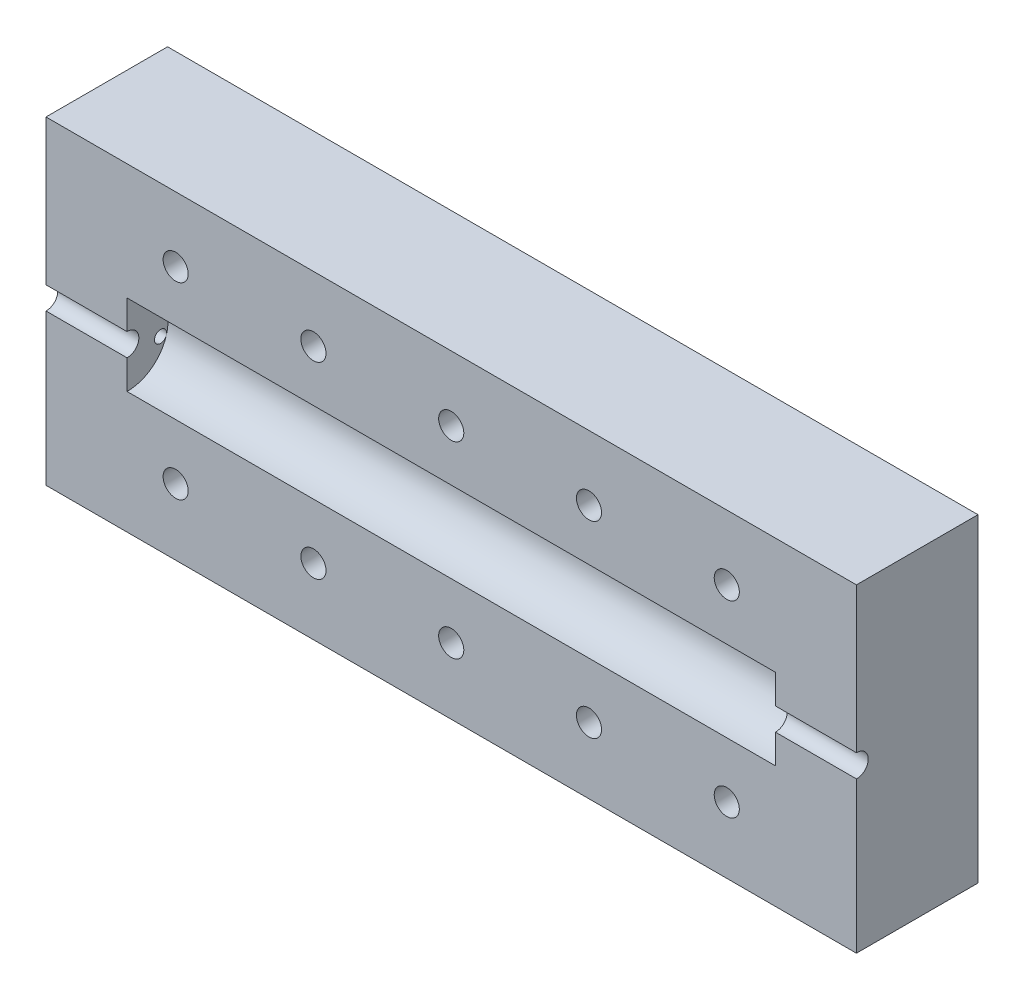
SolidWorks part; units mm, degrees
ref_plane "Ebene vorne" through (0, 0, 0) normal (0, 0, 1) x (1, 0, 0)
ref_plane "Ebene oben" through (0, 0, 0) normal (0, 1, 0) x (1, 0, 0)
ref_plane "Ebene rechts" through (0, 0, 0) normal (1, 0, 0) x (0, 0, -1)
sketch "Skizze2" plane through (0, 0, 0) normal (0, 0, 1) x (1, 0, 0)
  line L1 (0, 0) -> (100, 0)
  line L2 (0, 0) -> (0, 39.3642)
  line L3 (0, 39.3642) -> (100, 39.3642)
  line L4 (100, 0) -> (100, 39.3642)
  dimension "D1" = 39.3642
  dimension "D2" = 100
extrude "Aufsatz-Linear austragen1" add sketch "Skizze2" along normal blind 30
sketch "Skizze3" plane through (0, 0, 30) normal (0, 0, 1) x (1, 0, 0)
  line L0 (0, 19.6821) -> (100, 19.6821) construction
  line L1 (0, 39.3642) -> (0, 0) construction
  line L2 (100, 0) -> (100, 39.3642) construction
ref_plane "Ebene2" through (0, 19.7642, 0) normal (0, 1, 0) x (1, 0, 0)
sketch "Skizze9" plane through (0, 0, 30) normal (0, 0, 1) x (1, 0, 0)
  line L0 (50, 0) -> (50, 39.3642) construction
  line L1 (0, 0) -> (100, 0) construction
  line L2 (100, 39.3642) -> (0, 39.3642) construction
ref_plane "Ebene3" through (50, 0, 0) normal (-1, 0, 0) x (0, 0, 1)
sketch "Skizze10" plane through (50, 0, 0) normal (-1, 0, 0) x (0, 0, 1)
  line L0 (14.9458, 42.0451) -> (14.9458, -1.991) construction
  line L1 (-1.6741, 19.9497) -> (31.3778, 19.9497) construction
  circle A0 centre (14.9458, 20.027) radius 5
  dimension "D1" = 10
extrude "Schnitt-Linear austragen1" cut sketch "Skizze10" against normal blind 40 and the other way blind 40
ref_plane "Ebene4" through (90, 0, 0) normal (-1, 0, 0) x (0, 0, 1)
ref_plane "Ebene5" through (10, 0, 0) normal (-1, 0, 0) x (0, 0, 1)
sketch "Skizze17" plane through (90, 0, 0) normal (-1, 0, 0) x (0, 0, 1)
  circle A0 centre (14.9458, 20.027) radius 1.4
  dimension "D1" = 2.8
extrude "Schnitt-Linear austragen2" cut sketch "Skizze17" against normal through all
mirror "Spiegeln1" about plane through (50, 0, 0) normal (-1, 0, 0) of "Schnitt-Linear austragen2"
sketch "Skizze18" plane through (0, 39.3642, 0) normal (0, 1, 0) x (1, 0, 0)
  line L0 (100, -15) -> (0, -15) construction
  line L1 (100, -30) -> (100, 0) construction
ref_plane "Ebene6" through (0, 0, 15) normal (0, 0, -1) x (-1, 0, 0)
sketch "Skizze24" plane through (0, 0, 30) normal (0, 0, 1) x (1, 0, 0)
  line L0 (0, 39.3642) -> (0, 0) construction
  line L1 (100, 39.3642) -> (0, 39.3642) construction
  line L4 (100, 0) -> (100, 39.3642) construction
  circle A0 centre (16, 31.3642) radius 1.55
  circle A1 centre (33, 31.3642) radius 1.55
  circle A2 centre (50, 31.3642) radius 1.55
  circle A3 centre (67, 31.3642) radius 1.55
  circle A4 centre (84, 31.3642) radius 1.55
  dimension "D1" = 3.1
  dimension "D4" = 3.1
  dimension "D5" = 3.1
  dimension "D6" = 3.1
  dimension "D7" = 3.1
  dimension "D2" = 16
  dimension "D3" = 8
  dimension "D8" = 17
  dimension "D9" = 17
  dimension "D10" = 17
  dimension "D11" = 17
  dimension "D12" = 16
extrude "Schnitt-Linear austragen4" cut sketch "Skizze24" against normal through all
sketch "Skizze22" plane through (0, 0, 0) normal (-1, 0, 0) x (0, 0, 1)
  line L0 (30, 39.3642) -> (0, 39.3642) construction
  line L2 (0, 0) -> (0, 39.3642)
  line L5 (15, 0) -> (-1.8267, 0)
  line L6 (15, 0) -> (15, 39.3642)
  line L7 (15, 39.3642) -> (-1.8267, 39.3642)
  line L8 (-1.8267, 0) -> (-1.8267, 39.3642)
ref_plane "Ebene7" through (0, 0, 8.4) normal (0, 0, -1) x (-1, 0, 0)
ref_plane "Ebene8" through (16, 0, 0) normal (-1, 0, 0) x (0, 0, 1)
sketch "Skizze35" plane through (0, 0, 30) normal (0, 0, 1) x (1, 0, 0)
  line L0 (89.9018, 21.3451) -> (89.9018, 39.3769) construction
  line L1 (89.9018, 39.3769) -> (89.9018, 0) construction
  line L2 (0, 0) -> (100, 0) construction
ref_plane "Ebene9" through (90, 0, 0) normal (1, 0, 0) x (0, 0, -1)
sketch "Skizze36" plane through (90, 0, 0) normal (1, 0, 0) x (0, 0, -1)
  line L0 (-20.1004, 18.2046) -> (-18.9246, 18.6336)
  circle A0 centre (-18.9246, 18.6336) radius 0.75
  point P3 (-19.5125, 18.4191)
  dimension "D1" = 1.5
sketch "Skizze37" plane through (100, 0, 0) normal (1, 0, 0) x (0, 0, -1)
  circle A0 centre (-18.9246, 18.6336) radius 0.7369
extrude "Schnitt-Linear austragen9" cut sketch "Skizze37" against normal through all
sketch "Skizze40" plane through (100, 0, 0) normal (1, 0, 0) x (0, 0, -1)
  circle A0 centre (-18.9246, 18.6336) radius 2.1
  dimension "D1" = 4.2
extrude "Schnitt-Linear austragen10" cut sketch "Skizze40" against normal blind 6
sketch "Skizze42" plane through (0, 0, 0) normal (-1, 0, 0) x (0, 0, 1)
  line L0 (10.1439, 18.6336) -> (10.8642, 18.8426) construction
  circle A0 centre (14.9458, 20.027) radius 5 construction
  circle A1 centre (10.8642, 18.8426) radius 0.75
  dimension "D1" = 0.75
extrude "Schnitt-Linear austragen12" cut sketch "Skizze42" against normal blind 10
fillet "Verrundung1" radius 1 1 edges at (94, 18.6336, 18.1877)
sketch "Skizze46" plane through (0, 0, 0) normal (0, 0, -1) x (-1, 0, 0)
  circle A0 centre (-84, 31.3642) radius 2.85
  dimension "D1" = 5.7
extrude "Schnitt-Linear austragen15" cut sketch "Skizze46" against normal blind 10
sketch "Skizze50" plane through (0, 0, 30) normal (0, 0, 1) x (1, 0, 0)
  line L0 (81.15, 33.0096) -> (81.15, 39.3642)
  line L2 (81.15, 33.0096) -> (81.15, 29.7187)
  line L3 (81.15, 29.7187) -> (84, 28.0733)
  line L4 (84, 28.0733) -> (86.85, 29.7187)
  line L5 (86.85, 29.7187) -> (86.85, 33.0096)
  line L7 (100, 39.3642) -> (0, 39.3642) construction
  line L8 (81.15, 39.3642) -> (86.85, 39.3642)
  line L9 (86.85, 39.3642) -> (86.85, 33.0096)
  line L11 (84, 34.6551) -> (81.15, 33.0096) [skipped]
  line L12 (86.85, 33.0096) -> (84, 34.6551) [skipped]
  circle A0 centre (84, 31.3642) radius 2.85 construction
  dimension "D1" = 5.7
extrude "Schnitt-Linear austragen25" cut sketch "Skizze50" against normal blind 2.7 from offset 5 offset against normal yes
pattern_linear "Lineares Muster1" count 5 spacing 17 along (-1, 0, 0) of "Schnitt-Linear austragen25", "Schnitt-Linear austragen15"
mirror "Spiegeln2" about plane through (0, 19.7642, 0) normal (0, 1, 0) of "Lineares Muster1", "Schnitt-Linear austragen15", "Schnitt-Linear austragen25"
mirror "Spiegeln3" about plane through (0, 19.7642, 0) normal (0, 1, 0) of "Schnitt-Linear austragen4"
sketch "Skizze51" plane through (0, 0, 0) normal (-1, 0, 0) x (0, 0, 1)
  line L1 (15, 0) -> (30, 0)
  line L2 (15, 0) -> (15, 39.3642)
  line L3 (15, 39.3642) -> (30, 39.3642)
  line L4 (30, 0) -> (30, 39.3642)
extrude "Schnitt-Linear austragen26" cut sketch "Skizze51" against normal through all
